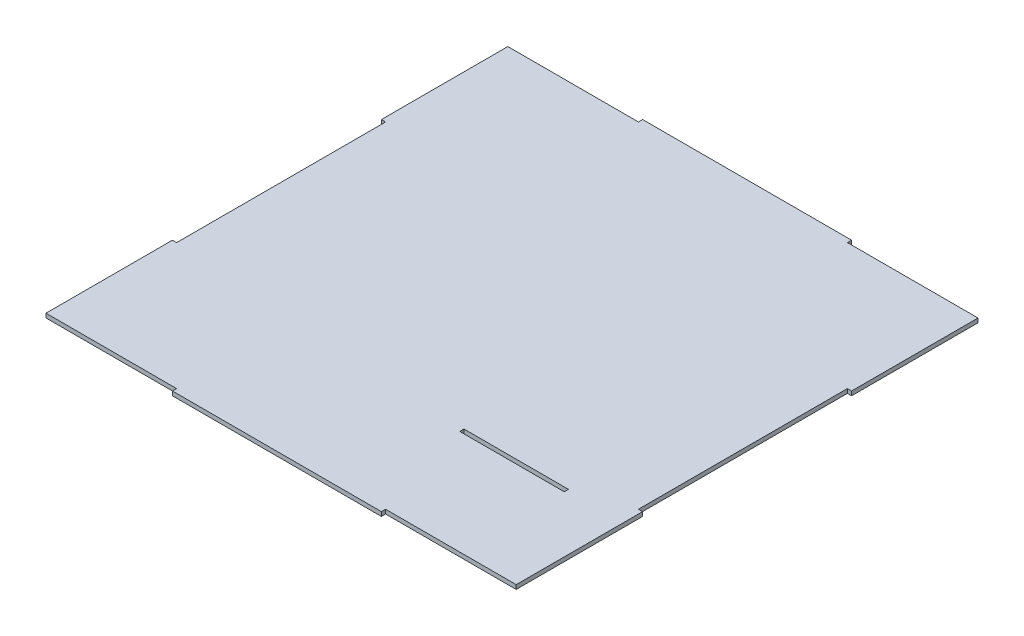
SolidWorks part; units mm, degrees
ref_plane "Front Plane" through (0, 0, 0) normal (0, 0, 1) x (1, 0, 0)
ref_plane "Top Plane" through (0, 0, 0) normal (0, 1, 0) x (1, 0, 0)
ref_plane "Right Plane" through (0, 0, 0) normal (1, 0, 0) x (0, 0, -1)
sketch "Sketch1" plane through (0, 0, 0) normal (0, 1, 0) x (1, 0, 0)
  line L0 (-225, 100) -> (-225, 221)
  line L1 (-100, -225) -> (100, -225)
  line L2 (-225, -221) -> (-225, -100)
  line L3 (-100, 225) -> (100, 225)
  line L4 (225, -221) -> (225, -100)
  line L6 (71, -117) -> (171, -117)
  line L7 (225, -100) -> (221, -100)
  line L9 (225, 100) -> (221, 100)
  line L10 (221, -100) -> (221, 100)
  line L11 (-100, 225) -> (100, 225)
  line L12 (-100, 225) -> (-100, 221)
  line L14 (100, 225) -> (100, 221)
  line L15 (-225, 100) -> (-221, 100)
  line L17 (-225, -100) -> (-221, -100)
  line L18 (-221, 100) -> (-221, -100)
  line L19 (-100, -225) -> (100, -225)
  line L20 (-100, -225) -> (-100, -221)
  line L22 (100, -225) -> (100, -221)
  line L23 (225, 100) -> (225, 221)
  line L24 (100, 221) -> (225, 221)
  line L25 (-100, 221) -> (-225, 221)
  line L26 (100, -221) -> (225, -221)
  line L27 (-100, -221) -> (-225, -221)
  line L28 (71, -117) -> (71, -121)
  line L29 (71, -121) -> (171, -121)
  line L30 (171, -117) -> (171, -121)
  point P0 (0, 0)
  point P22 (-221, 0)
  dimension "D2" = 200
  dimension "D3" = 200
  dimension "D4" = 4
  dimension "D5" = 4
  dimension "D6" = 100
  dimension "D7" = 100
  dimension "D8" = 200
  dimension "D9" = 4
  dimension "D10" = 200
  dimension "D11" = 4
  dimension "D12" = 100
  dimension "D13" = 100
  dimension "D14" = 121
  dimension "D15" = 121
  dimension "D16" = 450
  dimension "D17" = 100
  dimension "D18" = 4
  dimension "D19" = 100
  dimension "D20" = 442
  dimension "D21" = 50
extrude "Boss-Extrude1" add sketch "Sketch1" along normal blind 4 contours L27 L20 L1 L22 L26 L4 L7 L10 L9 L23 L24 L14 L3 L12 L25 L0 L15 L18 L17 L2 L6 L30 L29 L28
sketch "Sketch2" plane through (0, 4, 0) normal (0, 1, 0) x (1, 0, 0)
  line L20 (-225, -221) -> (-100, -221)
  line L21 (-100, -221) -> (-100, -225)
  line L22 (-100, -225) -> (100, -225)
  line L23 (100, -225) -> (100, -221)
  line L24 (100, -221) -> (225, -221)
  line L25 (225, -221) -> (225, -100)
  line L26 (225, -100) -> (221, -100)
  line L27 (221, -100) -> (221, 100)
  line L28 (221, 100) -> (225, 100)
  line L29 (225, 100) -> (225, 221)
  line L30 (225, 221) -> (100, 221)
  line L31 (100, 221) -> (100, 225)
  line L32 (100, 225) -> (-100, 225)
  line L33 (-100, 225) -> (-100, 221)
  line L34 (-100, 221) -> (-225, 221)
  line L35 (-225, 221) -> (-225, 100)
  line L36 (-225, 100) -> (-221, 100)
  line L37 (-221, 100) -> (-221, -100)
  line L38 (-221, -100) -> (-225, -100)
  line L39 (-225, -100) -> (-225, -221)
  line L40 (-225, -221) -> (-100, -221)
  line L41 (-100, -221) -> (-100, -225)
  line L42 (-100, -225) -> (100, -225)
  line L43 (100, -225) -> (100, -221)
  line L44 (100, -221) -> (225, -221)
  line L45 (225, -221) -> (225, -100)
  line L46 (225, -100) -> (221, -100)
  line L47 (221, -100) -> (221, 100)
  line L48 (221, 100) -> (225, 100)
  line L49 (225, 100) -> (225, 221)
  line L50 (225, 221) -> (100, 221)
  line L51 (100, 221) -> (100, 225)
  line L52 (100, 225) -> (-100, 225)
  line L53 (-100, 225) -> (-100, 221)
  line L54 (-100, 221) -> (-225, 221)
  line L55 (-225, 221) -> (-225, 100)
  line L56 (-225, 100) -> (-221, 100)
  line L57 (-221, 100) -> (-221, -100)
  line L58 (-221, -100) -> (-225, -100)
  line L59 (-225, -100) -> (-225, -221)
  dimension "D1" = 0
